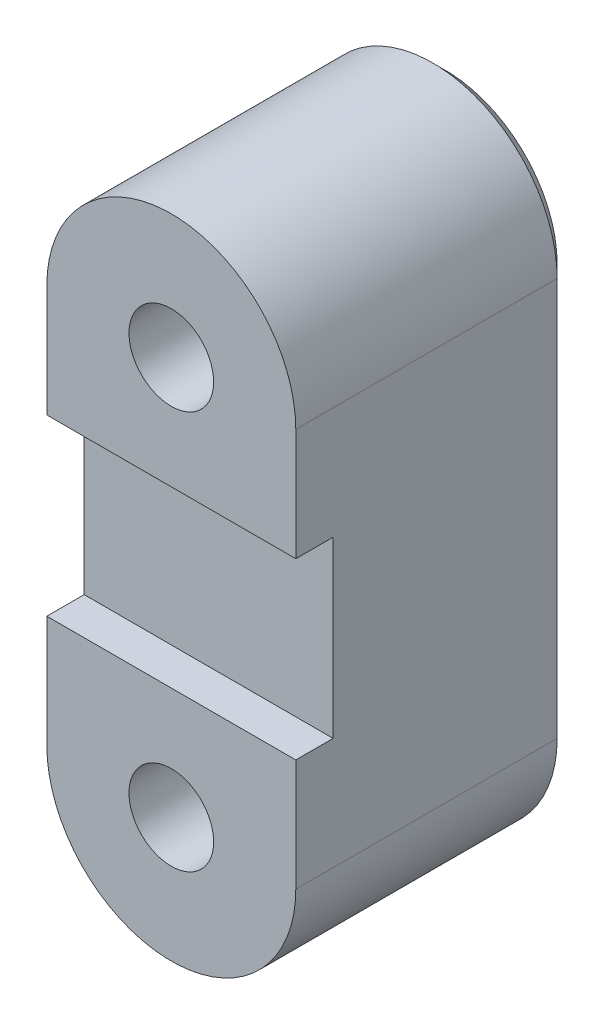
SolidWorks part; units mm, degrees
material "ABS"
ref_plane "Front Plane" through (0, 0, 0) normal (0, 0, 1) x (1, 0, 0)
ref_plane "Top Plane" through (0, 0, 0) normal (0, 1, 0) x (1, 0, 0)
ref_plane "Right Plane" through (0, 0, 0) normal (1, 0, 0) x (0, 0, -1)
sketch "Sketch1" plane through (0, 0, 0) normal (0, 0, 1) x (1, 0, 0)
  line L0 (0, -8) -> (0, 8) construction
  line L1 (0, -8) -> (0, 8) construction
  line L2 (-5, -8) -> (-5, 8)
  line L3 (5, -8) -> (5, 8)
  circle A0 centre (0, 8) radius 1.7
  circle A1 centre (0, -8) radius 1.7
  arc A2 (-5, -8) -> (5, -8) centre (0, -8) ccw
  arc A3 (5, 8) -> (-5, 8) centre (0, 8) ccw
  point P4 (0, 0)
  dimension "D1" = 3.4
  dimension "D2" = 5
  dimension "D3" = 16
extrude "Boss-Extrude1" add sketch "Sketch1" along normal blind 11
sketch "Sketch2" plane through (0, 0, 11) normal (0, 0, 1) x (1, 0, 0)
  line L0 (-5, 8) -> (-5, -8) construction
  line L1 (5, -8) -> (5, 8) construction
  line L2 (-5, -3.5) -> (5, -3.5)
  line L3 (-5, -3.5) -> (-5, 3.5)
  line L4 (-5, 3.5) -> (5, 3.5)
  line L5 (5, -3.5) -> (5, 3.5)
  line L6 (0, 0) -> (-5, 0) construction
  dimension "D1" = 7
extrude "Cut-Extrude1" cut sketch "Sketch2" against normal blind 1.5
chamfer "Chamfer1" distance 0.5 angle 45 6 edges at (1.7, -8, 0) (1.7, 8, 0) (5, 0, 0) (0, -13, 0) (-5, 0, 0) (0, 13, 0)
